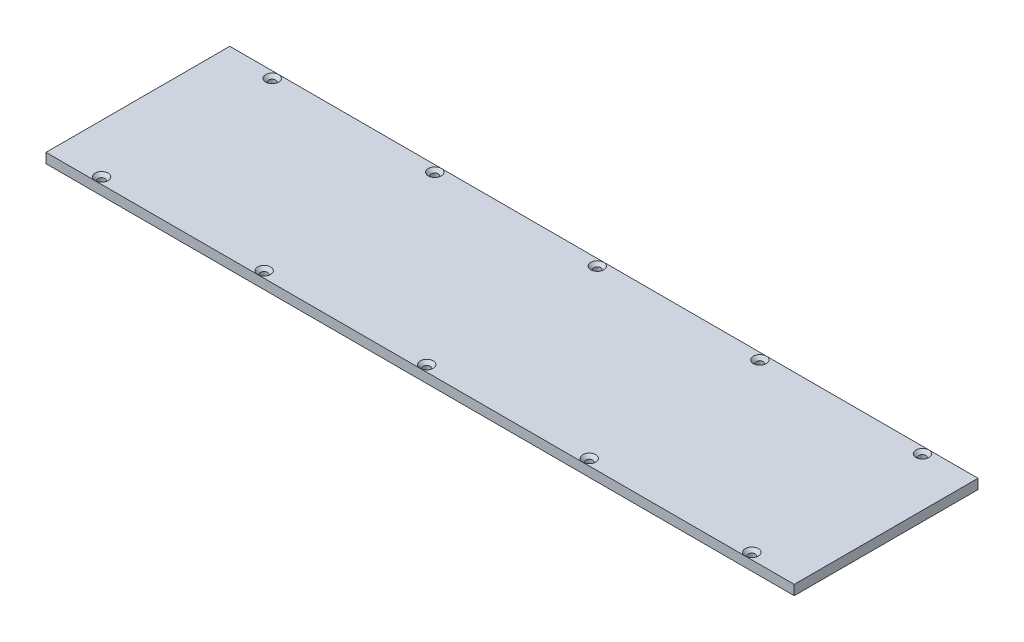
SolidWorks part; units mm, degrees
material "Wood floor laminate, Egger MED"
ref_plane "Front Plane" through (0, 0, 0) normal (0, 0, 1) x (1, 0, 0)
ref_plane "Top Plane" through (0, 0, 0) normal (0, 1, 0) x (1, 0, 0)
ref_plane "Right Plane" through (0, 0, 0) normal (1, 0, 0) x (0, 0, -1)
sketch "Sketch1" plane through (0, 0, 0) normal (0, 1, 0) x (1, 0, 0)
  line L1 (-361.95, -88.9) -> (361.95, -88.9)
  line L2 (-361.95, -88.9) -> (-361.95, 88.9)
  line L3 (-361.95, 88.9) -> (361.95, 88.9)
  line L4 (361.95, -88.9) -> (361.95, 88.9)
  line L5 (0, 88.9) -> (0, -88.9) construction
  line L6 (-361.95, 0) -> (361.95, 0) construction
  point P0 (0, 0)
  dimension "D1" = 723.9
  dimension "D2" = 177.8
extrude "Boss-Extrude1" add sketch "Sketch1" along normal blind 9.525
sketch "Sketch2" plane through (0, 9.525, 0) normal (0, 1, 0) x (1, 0, 0)
  line L0 (-361.95, -88.9) -> (361.95, -88.9) construction
  line L1 (-361.95, -88.9) -> (361.95, -88.9) construction
  line L2 (-361.95, -88.9) -> (-361.95, 88.9) construction
  line L3 (-361.95, 88.9) -> (361.95, 88.9) construction
  line L4 (361.95, -88.9) -> (361.95, 88.9) construction
  line L5 (0, 88.9) -> (0, -88.9) construction
  line L6 (-361.95, 0) -> (361.95, 0) construction
  line L7 (361.95, -88.9) -> (361.95, 88.9) construction
  line L8 (361.95, 88.9) -> (-361.95, 88.9) construction
  line L9 (-361.95, 88.9) -> (-361.95, -88.9) construction
  line L12 (-320.8936, -82.55) -> (320.8936, -82.55) construction
  line L14 (-355.6, -82.55) -> (-355.6, 82.55) construction
  line L15 (355.6, -82.55) -> (355.6, 82.55) construction
  line L16 (-320.8936, 82.55) -> (-320.8936, -82.55) construction
  line L18 (-355.6, 82.55) -> (355.6, 82.55) construction
  line L19 (-355.6, -82.55) -> (355.6, -82.55) construction
  line L20 (320.8936, 82.55) -> (320.8936, -82.55) construction
  line L21 (-314.5436, 82.55) -> (0, 82.55) construction
  line L22 (0, 82.55) -> (314.5436, 82.55) construction
  line L23 (-314.5436, 82.55) -> (-314.5436, -82.55) construction
  line L24 (314.5436, 82.55) -> (314.5436, -82.55) construction
  line L25 (-320.8936, 82.55) -> (-314.5436, 82.55) construction
  line L26 (314.5436, 82.55) -> (320.8936, 82.55) construction
  point P16 (-157.2718, 82.55)
  point P17 (157.2718, 82.55)
  point P19 (-157.2718, -82.55)
  point P20 (157.2718, -82.55)
  point P201 (314.5436, -82.55)
  point P203 (-314.5436, 82.55)
  point P205 (-314.5436, -82.55)
  point P207 (0, -82.55)
  point P209 (0, 82.55)
  point P211 (314.5436, 82.55)
  dimension "D2" = 320.8936
  dimension "D3" = 320.8936
  dimension "D4" = 6.35
  dimension "D1" = 6.35
  dimension "D5" = 6.35
  dimension "D6" = 6.35
hole_wizard "CSK for M6 Flat Head Machine Screw1" positions "Sketch2" profile "Sketch3" countersink size "M6" standard "ANSI Metric" end condition through all
sketch "Sketch3" plane through (314.5436, 9.525, -82.55) normal (1, 0, 0) x (0, 0, 1)
  line L0 (0, 0) -> (0, 9.525)
  line L1 (0, 9.525) -> (3.3, 9.525)
  line L2 (3.3, 9.525) -> (3.3, 3)
  line L3 (3.3, 3) -> (6.3, 0)
  line L5 (6.3, 0) -> (0, 0)
  line L6 (-3.3, 3) -> (-6.3, 0) construction
  line L11 (0, -6.35) -> (0, 107.95) construction
  dimension "Thru Hole Dia." = 6.6
  dimension "Thru Hole Depth" = 9.525
  dimension "Near C'Sink Dia." = 12.6
  dimension "Near C'Sink Angle" = 90
